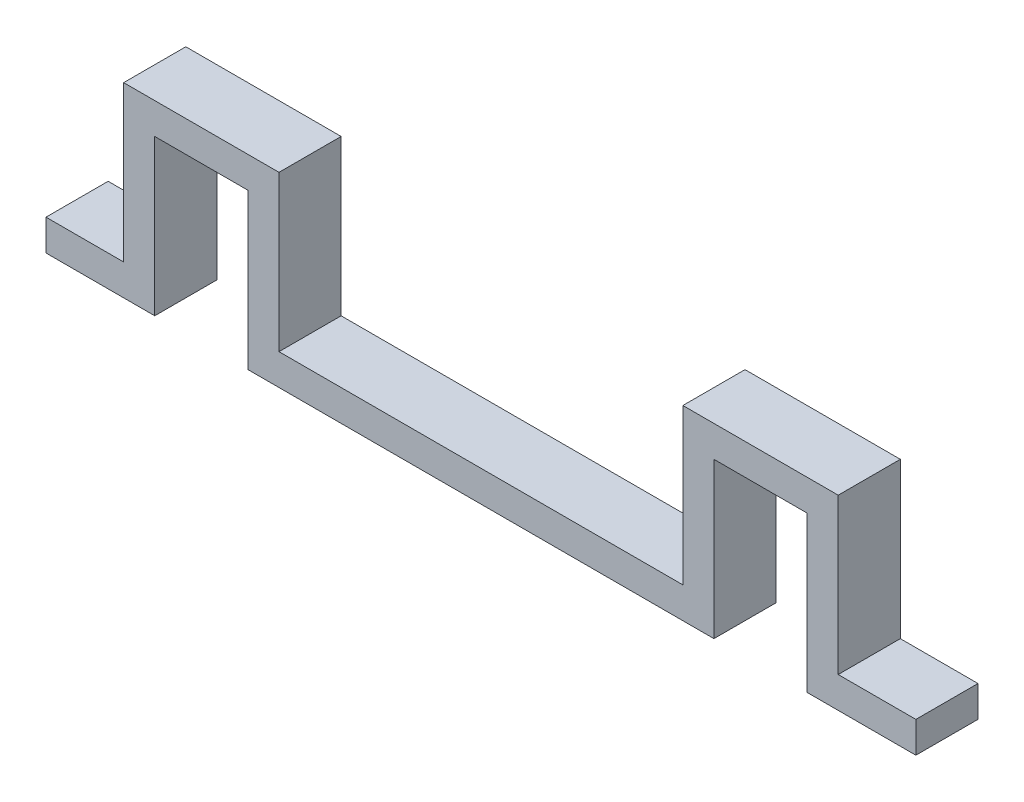
SolidWorks part; units mm, degrees
material "Brass"
ref_plane "Front Plane" through (0, 0, 0) normal (0, 0, 1) x (1, 0, 0)
ref_plane "Top Plane" through (0, 0, 0) normal (0, 1, 0) x (1, 0, 0)
ref_plane "Right Plane" through (0, 0, 0) normal (1, 0, 0) x (0, 0, -1)
sketch "Sketch1" plane through (0, 0, 0) normal (0, 0, 1) x (1, 0, 0)
  line L0 (-182.1994, -97.9006) -> (-169.6994, -97.9006)
  line L1 (-169.6994, -97.9006) -> (-169.6994, -72.9006)
  line L2 (-169.6994, -72.9006) -> (-144.6994, -72.9006)
  line L3 (-144.6994, -72.9006) -> (-144.6994, -97.9006)
  line L4 (-144.6994, -97.9006) -> (-79.6994, -97.9006)
  line L5 (-79.6994, -97.9006) -> (-79.6994, -72.9006)
  line L6 (-79.6994, -72.9006) -> (-54.6994, -72.9006)
  line L7 (-54.6994, -72.9006) -> (-54.6994, -97.9006)
  line L8 (-54.6994, -97.9006) -> (-42.1994, -97.9006)
  line L9 (-182.1994, -102.9006) -> (-164.6994, -102.9006)
  line L10 (-164.6994, -102.9006) -> (-164.6994, -77.9006)
  line L11 (-164.6994, -77.9006) -> (-149.6994, -77.9006)
  line L12 (-149.6994, -77.9006) -> (-149.6994, -102.9006)
  line L13 (-149.6994, -102.9006) -> (-74.6994, -102.9006)
  line L14 (-74.6994, -102.9006) -> (-74.6994, -77.9006)
  line L15 (-74.6994, -77.9006) -> (-59.6994, -77.9006)
  line L16 (-59.6994, -77.9006) -> (-59.6994, -102.9006)
  line L17 (-59.6994, -102.9006) -> (-42.1994, -102.9006)
  line L18 (-182.1994, -97.9006) -> (-182.1994, -102.9006)
  line L19 (-42.1994, -97.9006) -> (-42.1994, -102.9006)
  dimension "D2" = 75
  dimension "D3" = 17.5
  dimension "D4" = 15
  dimension "D5" = 140
  dimension "D6" = 25
  dimension "D7" = 25
  dimension "D1" = 17.5
  dimension "D8" = 25
extrude "Boss-Extrude1" add sketch "Sketch1" along normal blind 10
